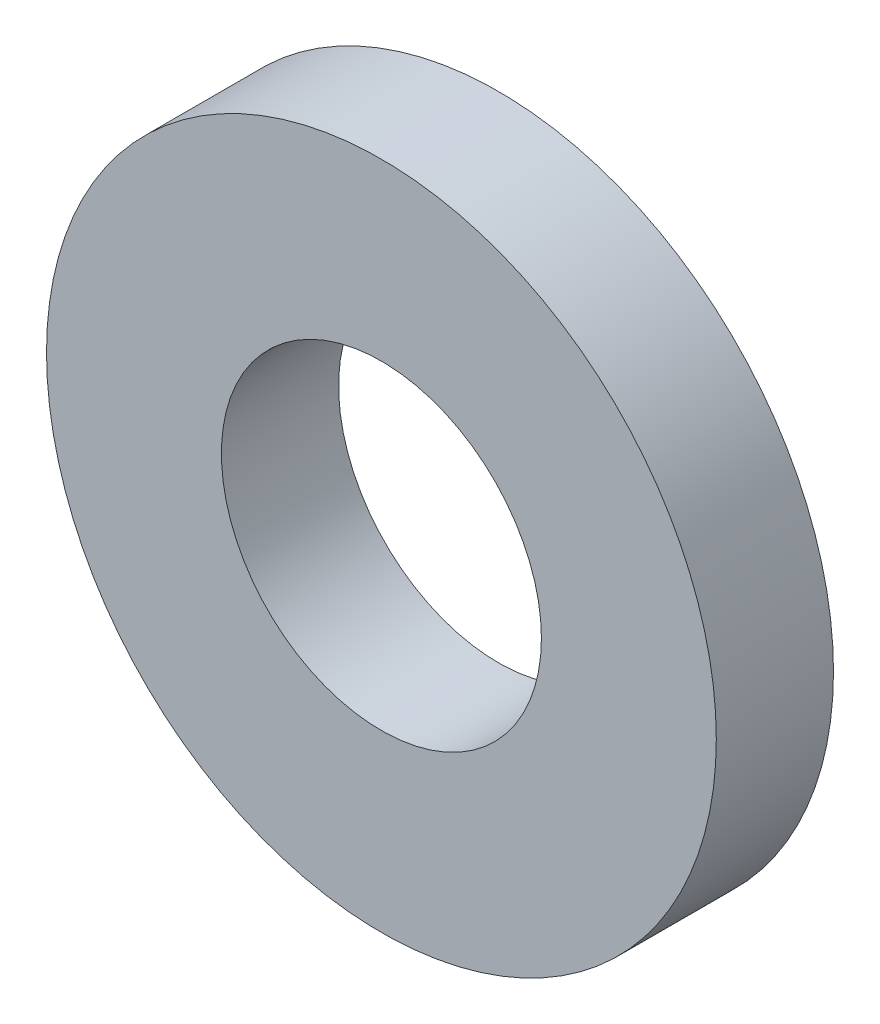
SolidWorks part; units mm, degrees
ref_plane "Front Plane" through (0, 0, 0) normal (0, 0, 1) x (1, 0, 0)
ref_plane "Top Plane" through (0, 0, 0) normal (0, 1, 0) x (1, 0, 0)
ref_plane "Right Plane" through (0, 0, 0) normal (1, 0, 0) x (0, 0, -1)
sketch "Sketch1" plane through (0, 0, 0) normal (0, 1, 0) x (1, 0, 0)
  line L0 (0, 0) -> (-2.15, 0) construction
  line L1 (0, 0) -> (2.15, 0) construction
  line L2 (2.15, 0) -> (4.5, 0) construction
  line L3 (-2.15, 0) -> (-4.5, 0) construction
  dimension "ID" = 4.3
  dimension "OD" = 9
sketch "Sketch2" plane through (0, 0, 0) normal (1, 0, 0) x (0, 0, -1)
  line L1 (0.7873, -4.5) -> (-0.7872, -4.5) construction
  line L2 (0.7873, -4.5) -> (0.7873, 4.5) construction
  line L3 (0.7873, 4.5) -> (-0.7872, 4.5) construction
  line L4 (-0.7872, -4.5) -> (-0.7872, 4.5) construction
  line L5 (0.7873, -4.5) -> (-0.7872, 4.5) construction
  line L6 (0.7873, 4.5) -> (-0.7872, -4.5) construction
  point P0 (0, 0)
  dimension "Thickness" = 1.5745
  dimension "D1" = 9
sketch "Sketch3" plane through (0, 0, 0) normal (0, 0, 1) x (1, 0, 0)
  line L0 (0, -4.5) -> (0, 4.5) construction
  circle A0 centre (0, 0) radius 4.5
  circle A1 centre (0, 0) radius 2.15
extrude "Boss-Extrude3" add sketch "Sketch3" against normal up to vertex (0.7873 mm away) and the other way up to vertex (0.7873 mm away) up to point (0, 4.5, -0.7873) other way up to point (0, 4.5, 0.7872)
equation "\"D1@Sketch2\"=\"OD@Sketch1\""
